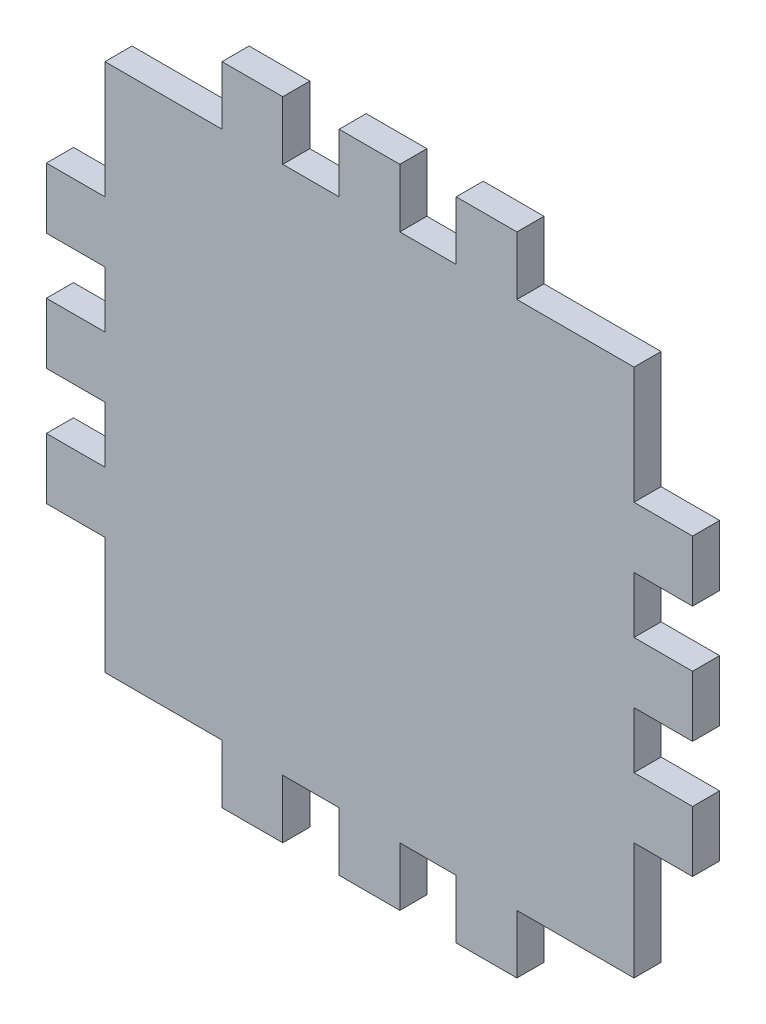
SolidWorks part; units mm, degrees
ref_plane "Front Plane" through (0, 0, 0) normal (0, 0, 1) x (1, 0, 0)
ref_plane "Top Plane" through (0, 0, 0) normal (0, 1, 0) x (1, 0, 0)
ref_plane "Right Plane" through (0, 0, 0) normal (1, 0, 0) x (0, 0, -1)
sketch "Model" plane through (0, 0, 0) normal (0, 0, 1) x (1, 0, 0)
  line L0 (266.5333, 180.0361) -> (266.5333, 196.3361)
  line L1 (266.5333, 140.3361) -> (266.5333, 124.0361)
  line L2 (194.2333, 196.3361) -> (210.2333, 196.3361)
  line L3 (210.2333, 196.3361) -> (210.2333, 204.3361)
  line L4 (210.2333, 204.3361) -> (218.5333, 204.3361)
  line L5 (218.5333, 204.3361) -> (218.5333, 196.3361)
  line L6 (218.5333, 196.3361) -> (226.2333, 196.3361)
  line L7 (226.2333, 196.3361) -> (226.2333, 204.3361)
  line L8 (226.2333, 204.3361) -> (234.5333, 204.3361)
  line L9 (234.5333, 204.3361) -> (234.5333, 196.3361)
  line L10 (234.5333, 196.3361) -> (242.2333, 196.3361)
  line L11 (242.2333, 196.3361) -> (242.2333, 204.3361)
  line L12 (242.2333, 204.3361) -> (250.5333, 204.3361)
  line L13 (250.5333, 204.3361) -> (250.5333, 196.3361)
  line L14 (250.5333, 196.3361) -> (266.5333, 196.3361)
  line L15 (194.2333, 140.3361) -> (194.2333, 124.0361)
  line L16 (194.2333, 180.0361) -> (194.2333, 196.3361)
  line L19 (266.5333, 140.0361) -> (266.5333, 124.0361)
  line L20 (274.5333, 140.0361) -> (266.5333, 140.0361)
  line L22 (274.5333, 148.3361) -> (274.5333, 140.0361)
  line L23 (266.5333, 148.3361) -> (274.5333, 148.3361)
  line L24 (266.5333, 156.0361) -> (266.5333, 148.3361)
  line L26 (274.5333, 156.0361) -> (266.5333, 156.0361)
  line L27 (266.5333, 164.3361) -> (274.5333, 164.3361)
  line L28 (266.5333, 172.0361) -> (266.5333, 164.3361)
  line L30 (274.5333, 172.0361) -> (266.5333, 172.0361)
  line L31 (274.5333, 180.3361) -> (274.5333, 172.0361)
  line L32 (266.5333, 196.3361) -> (266.5333, 180.3361)
  line L33 (266.5333, 180.3361) -> (274.5333, 180.3361)
  line L34 (194.2333, 180.3361) -> (194.2333, 196.3361)
  line L35 (186.2333, 180.3361) -> (194.2333, 180.3361)
  line L36 (266.5333, 124.0361) -> (250.5333, 124.0361)
  line L37 (250.5333, 124.0361) -> (250.5333, 116.0361)
  line L38 (250.5333, 116.0361) -> (242.2333, 116.0361)
  line L39 (242.2333, 116.0361) -> (242.2333, 124.0361)
  line L40 (242.2333, 124.0361) -> (234.5333, 124.0361)
  line L41 (234.5333, 124.0361) -> (234.5333, 116.0361)
  line L42 (234.5333, 116.0361) -> (226.2333, 116.0361)
  line L43 (226.2333, 116.0361) -> (226.2333, 124.0361)
  line L44 (226.2333, 124.0361) -> (218.5333, 124.0361)
  line L45 (218.5333, 124.0361) -> (218.5333, 116.0361)
  line L46 (218.5333, 116.0361) -> (210.2333, 116.0361)
  line L47 (210.2333, 116.0361) -> (210.2333, 124.0361)
  line L48 (210.2333, 124.0361) -> (194.2333, 124.0361)
  line L49 (186.2333, 172.0361) -> (186.2333, 180.3361)
  line L50 (194.2333, 172.0361) -> (186.2333, 172.0361)
  line L51 (194.2333, 164.3361) -> (194.2333, 172.0361)
  line L52 (186.2333, 164.3361) -> (194.2333, 164.3361)
  line L53 (186.2333, 156.0361) -> (186.2333, 164.3361)
  line L54 (194.2333, 156.0361) -> (186.2333, 156.0361)
  line L56 (194.2333, 148.3361) -> (194.2333, 156.0361)
  line L57 (186.2333, 148.3361) -> (194.2333, 148.3361)
  line L58 (186.2333, 140.0361) -> (186.2333, 148.3361)
  line L60 (194.2333, 140.0361) -> (186.2333, 140.0361)
  line L61 (194.2333, 124.0361) -> (194.2333, 140.0361)
  line L62 (274.5333, 156.0361) -> (274.5333, 164.3361)
  point P72 (230.3833, 160.1861)
  dimension "D1" = 2
extrude "Boss-Extrude1" add sketch "Model" along normal blind 3.7
